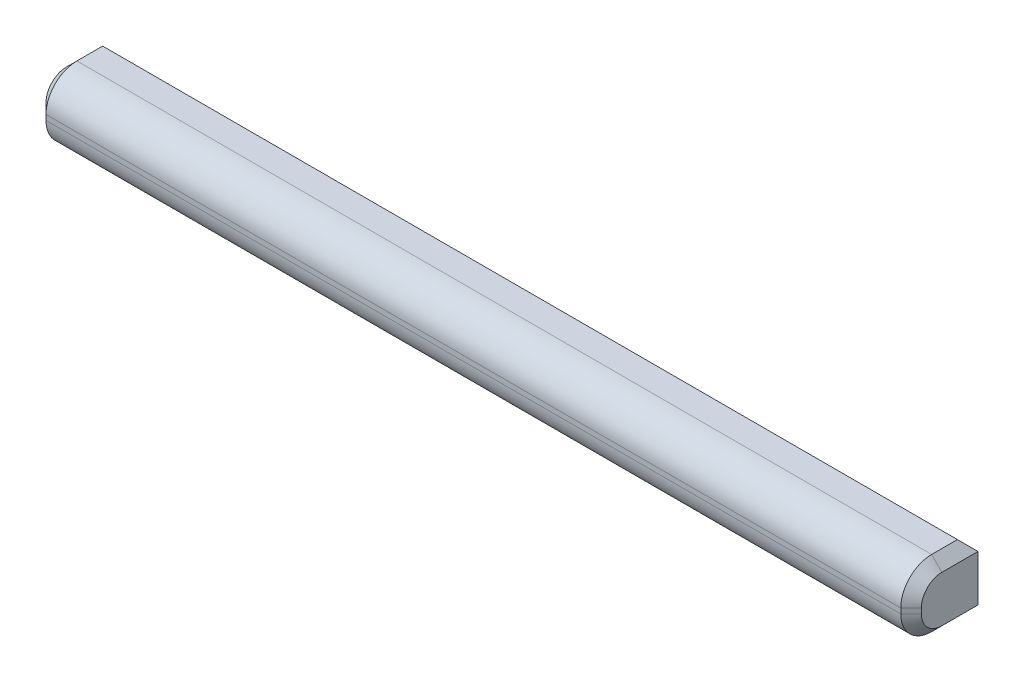
SolidWorks part; units mm, degrees
ref_plane "Alzado" through (0, 0, 0) normal (0, 0, 1) x (1, 0, 0)
ref_plane "Planta" through (0, 0, 0) normal (0, 1, 0) x (1, 0, 0)
ref_plane "Vista lateral" through (0, 0, 0) normal (1, 0, 0) x (0, 0, -1)
sketch "Croquis2" plane through (0, 0, 0) normal (1, 0, 0) x (0, 0, -1)
  line L1 (0, 0) -> (-6.5, 0)
  line L2 (0, 0) -> (0, 6.5)
  line L3 (0, 6.5) -> (-6.5, 6.5)
  line L4 (-6.5, 0) -> (-6.5, 6.5)
  dimension "D1" = 6.5
  dimension "D2" = 6.5
extrude "Saliente-Extruir1" add sketch "Croquis2" along normal blind 85
fillet "Redondeo1" radius 3 2 edges at (42.5, 0, 6.5) (42.5, 6.5, 6.5)
chamfer "Chaflán1" distance 1 angle 45 12 edges at (42.5, 6.5, 0) (85, 6.5, 1.75) (0, 6.5, 1.75) (85, 5.6213, 5.6213) (0, 5.6213, 5.6213) (85, 0.8787, 5.6213) (0, 0.8787, 5.6213) (85, 0, 1.75) (42.5, 0, 0) (0, 0, 1.75) (85, 3.25, 6.5) (0, 3.25, 6.5)
equation "\"D1@Croquis2\"=\"D2@Croquis2\""
